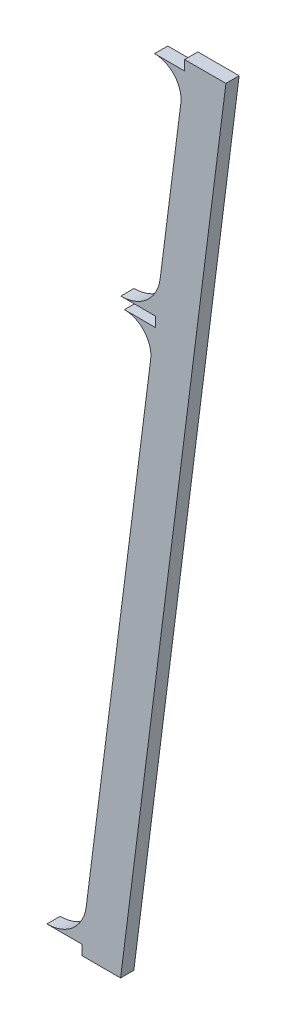
SolidWorks part; units mm, degrees
ref_plane "前视基准面" through (0, 0, 0) normal (0, 0, 1) x (1, 0, 0)
ref_plane "上视基准面" through (0, 0, 0) normal (0, 1, 0) x (1, 0, 0)
ref_plane "右视基准面" through (0, 0, 0) normal (1, 0, 0) x (0, 0, -1)
sketch "草图1" plane through (0, 0, 0) normal (0, 0, 1) x (1, 0, 0)
  line L0 (21.7406, 126.2167) -> (20.2821, 126.2167)
  line L1 (26.2821, 127.7167) -> (32.5215, 127.7167)
  line L2 (32.5215, 127.7167) -> (16.6093, 2.7167)
  line L3 (5.4672, 4.2167) -> (4.7518, 4.2167)
  line L4 (10.7518, 2.7167) -> (16.6093, 2.7167)
  line L5 (11.4191, 9.459) -> (21.1552, 85.9416)
  line L6 (16.635, 91.9467) -> (15.9196, 91.9467)
  line L7 (15.9196, 90.4467) -> (17.1872, 90.4467)
  line L8 (25.7086, 121.7116) -> (22.587, 97.189)
  line L9 (15.9196, 91.9467) -> (21.9196, 91.9467)
  line L10 (21.9196, 91.9467) -> (21.9196, 90.4467)
  line L11 (21.9196, 90.4467) -> (15.9196, 90.4467)
  line L12 (4.7518, 4.2167) -> (10.7518, 4.2167)
  line L13 (10.7518, 4.2167) -> (10.7518, 2.7167)
  line L14 (20.2821, 126.2167) -> (26.2821, 126.2167)
  line L15 (26.2821, 126.2167) -> (26.2821, 127.7167)
  arc A0 (5.4672, 4.2167) -> (11.4191, 9.459) centre (5.4672, 10.2167) ccw
  arc A1 (21.1552, 85.9416) -> (17.1872, 90.4467) centre (17.1872, 86.4467) ccw
  arc A2 (16.635, 91.9467) -> (22.587, 97.189) centre (16.635, 97.9467) ccw
  arc A3 (25.7086, 121.7116) -> (21.7406, 126.2167) centre (21.7406, 122.2167) ccw
extrude "凸台-拉伸1" add sketch "草图1" along normal blind 2 contours A3 L8 A2 L9 L10 L11 A1 L5 A0 L12 L13 L4 L2 L1 L15 L14
